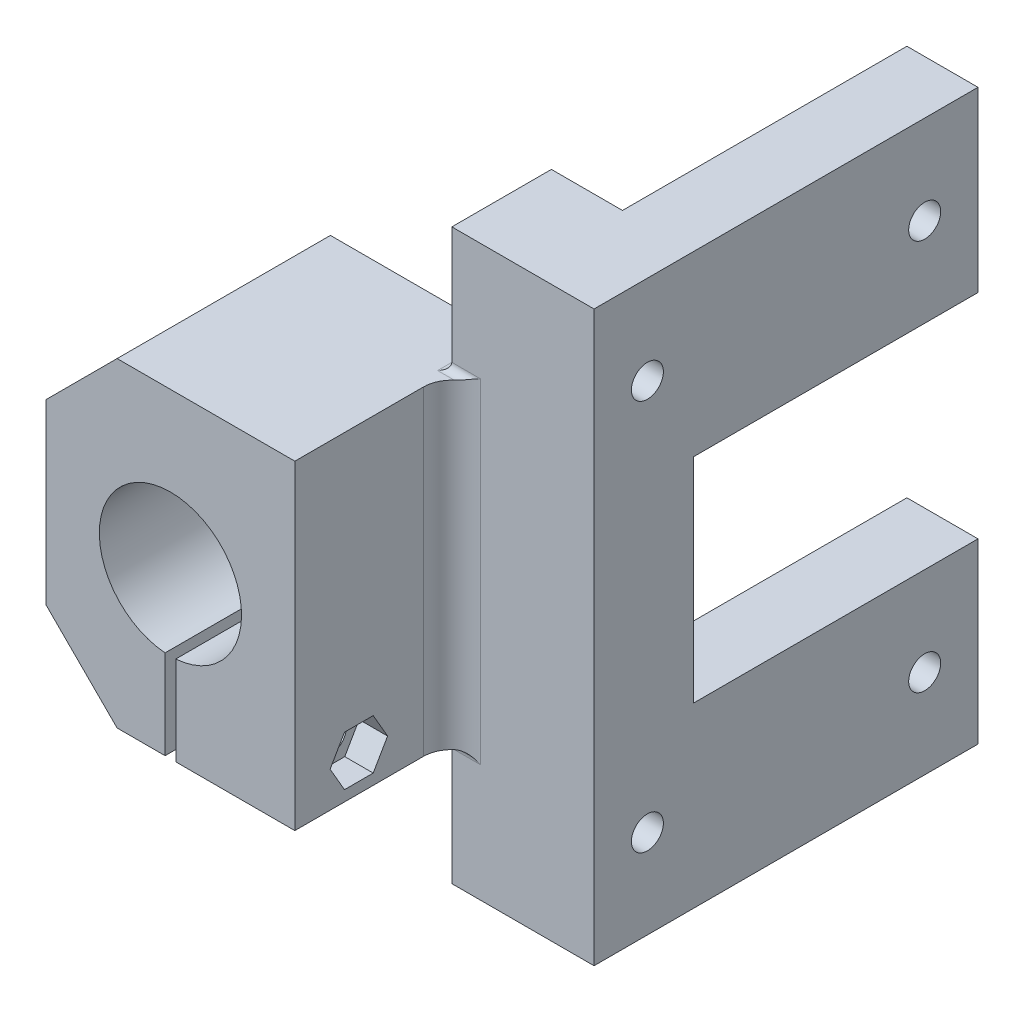
SolidWorks part; units mm, degrees
ref_plane "Plan de face" through (0, 0, 0) normal (0, 0, 1) x (1, 0, 0)
ref_plane "Plan de dessus" through (0, 0, 0) normal (0, 1, 0) x (1, 0, 0)
ref_plane "Plan de droite" through (0, 0, 0) normal (1, 0, 0) x (0, 0, -1)
sketch "Sketch1" plane through (0, 0, 0) normal (0, 0, 1) x (1, 0, 0)
  line L1 (17.5, -22.5) -> (-17.5, -22.5)
  line L2 (17.5, -22.5) -> (17.5, 22.5)
  line L3 (17.5, 22.5) -> (-17.5, 22.5)
  line L4 (-17.5, -22.5) -> (-17.5, 22.5)
  line L5 (17.5, -22.5) -> (-17.5, 22.5) construction
  line L6 (17.5, 22.5) -> (-17.5, -22.5) construction
  circle A0 centre (0, 0) radius 10
  dimension "D1" = 20
  dimension "D2" = 35
  dimension "D3" = 45
extrude "Boss-Extrude1" add sketch "Sketch1" along normal blind 30
sketch "Sketch2" plane through (17.5, 0, 0) normal (1, 0, 0) x (0, 0, -1)
  line L1 (-7.9199, -40) -> (46.0801, -40)
  line L2 (-7.9199, -40) -> (-7.9199, 40)
  line L3 (-7.9199, 40) -> (46.0801, 40)
  line L4 (46.0801, -40) -> (46.0801, 40)
  circle A0 centre (-0.4199, 27.5) radius 2.25
  circle A1 centre (38.5801, 27.5) radius 2.25
  circle A2 centre (38.5801, -27.5) radius 2.25
  circle A3 centre (-0.4199, -27.5) radius 2.25
extrude "Boss-Extrude2" add sketch "Sketch2" along normal blind 20
sketch "Sketch3" plane through (17.5, 0, 0) normal (-1, 0, 0) x (0, 0, 1)
  line L0 (7.9199, -40) -> (-46.0801, -40) construction
  line L1 (-46.0801, 40) -> (-6.0801, 40)
  line L2 (-46.0801, 40) -> (-46.0801, -40)
  line L3 (-46.0801, -40) -> (-6.0801, -40)
  line L4 (-6.0801, 40) -> (-6.0801, -40)
  dimension "D1" = 40
extrude "Cut-Extrude1" cut sketch "Sketch3" against normal blind 10
sketch "Sketch5" plane through (37.5, 0, 0) normal (1, 0, 0) x (0, 0, -1)
  line L0 (46.0801, -40) -> (46.0801, 40) construction
  line L1 (46.0801, -15) -> (6.0801, -15)
  line L2 (46.0801, -15) -> (46.0801, 15)
  line L3 (46.0801, 15) -> (6.0801, 15)
  line L4 (6.0801, -15) -> (6.0801, 15)
  line L5 (46.0801, 40) -> (-7.9199, 40) construction
  line L6 (-7.9199, -40) -> (46.0801, -40) construction
  point P6 (0, 0)
  point P7 (46.08, -14.2432)
  point P8 (46.08, -14.987)
  point P9 (46.08, -14.4378)
  dimension "D1" = 40
  dimension "D2" = 25
  dimension "D3" = 25
extrude "Cut-Extrude2" cut sketch "Sketch5" against normal blind 10
fillet "Fillet1" radius 4 2 edges at (17.5, 0, 7.9199) (17.5, 0, 0)
fillet "Fillet2" radius 1 4 edges at (17.5, -22.5, 1.96) (19.5, -22.5, 7.9199) (17.5, 22.5, 1.96) (19.5, 22.5, 7.9199)
chamfer "Chamfer1" distance 10 angle 45 2 edges at (-17.5, 22.5, 15) (-17.5, -22.5, 15)
sketch "Sketch6" plane through (17.5, 0, 0) normal (1, 0, 0) x (0, 0, -1)
  line L0 (-30, -22.5) -> (-11.9199, -22.5) construction
  line L1 (-18.9793, -21) -> (-16.9585, -17.5)
  line L2 (-16.9585, -17.5) -> (-18.9793, -14)
  line L3 (-18.9793, -14) -> (-23.0207, -14)
  line L4 (-23.0207, -14) -> (-25.0415, -17.5)
  line L5 (-25.0415, -17.5) -> (-23.0207, -21)
  line L6 (-23.0207, -21) -> (-18.9793, -21)
  line L7 (-30, -22.5) -> (-30, 22.5) construction
  circle A0 centre (-21, -17.5) radius 3.5 construction
  dimension "D1" = 7
  dimension "D2" = 5
  dimension "D3" = 9
extrude "Cut-Extrude3" cut sketch "Sketch6" against normal blind 4
ref_plane "Plane1" through (-7.5, 0, 0) normal (1, 0, 0) x (0, 0, -1)
hole_wizard "Chambrage pour vis à six pans creux M41" positions "Sketch9" profile "Sketch10" counterbore size "M4" standard "ISO"
sketch "Sketch9" plane through (-7.5, 0, 0) normal (1, 0, 0) x (0, 0, -1)
  line L0 (-30, -22.5) -> (-11.9199, -22.5) construction
  line L1 (-30, -22.5) -> (-30, 22.5) construction
  point P0 (-21, -17.5)
  point P10 (-22.1263, -17.9319)
  dimension "D1" = 5
  dimension "D2" = 9
sketch "Sketch10" plane through (-7.5, -17.5, 21) normal (0, 1, 0) x (0, 0, 1)
  line L0 (0, 0) -> (0, 45)
  line L1 (0, 45) -> (2.25, 45)
  line L3 (2.25, 45) -> (2.25, 4.4)
  line L4 (2.25, 4.4) -> (4, 4.4)
  line L5 (4, 4.4) -> (4, 0)
  line L7 (4, 0) -> (0, 0)
  line L11 (0, -6.35) -> (0, 107.95) construction
  dimension "Diamètre du perçage jusqu'au prochain" = 4.5
  dimension "Profondeur du perçage jusqu'au prochain" = 45
  dimension "Diamètre du chambrage" = 8
  dimension "Profondeur du chambrage" = 4.4
sketch "Sketch11" plane through (-7.5, 0, 0) normal (1, 0, 0) x (0, 0, -1)
  circle A0 centre (-21, -17.5) radius 4
  dimension "D1" = 8
extrude "Cut-Extrude4" cut sketch "Sketch11" against normal through all
sketch "Sketch12" plane through (0, 0, 30) normal (0, 0, 1) x (1, 0, 0)
  line L0 (0.75, -9.9718) -> (0.75, -31.545)
  line L3 (-0.75, -31.545) -> (0.75, -31.545)
  line L6 (-0.75, -31.545) -> (0, 0) construction
  line L8 (0, 0) -> (0.75, -31.545) construction
  line L9 (-0.75, -9.9718) -> (-0.75, -31.545)
  arc A2 (-0.75, -9.9718) -> (0.75, -9.9718) centre (0, 0) ccw
  point P0 (0, 0)
  dimension "D1" = 1.5
extrude "Cut-Extrude5" cut sketch "Sketch12" against normal through all
hole_wizard "Chambrage pour vis à six pans creux M42" positions "Sketch13" profile "Sketch14" counterbore size "M4" standard "ISO" end condition through all
sketch "Sketch13" plane through (17.5, 0, 0) normal (-1, 0, 0) x (0, 0, 1)
  point P0 (0.4199, -27.5)
  point P3 (0.4199, 27.5)
sketch "Sketch14" plane through (17.5, -27.5, 0.4199) normal (0, 1, 0) x (0, 0, 1)
  line L0 (0, 0) -> (0, 20)
  line L1 (0, 20) -> (2.25, 20)
  line L3 (2.25, 20) -> (2.25, 4.4)
  line L4 (2.25, 4.4) -> (4, 4.4)
  line L5 (4, 4.4) -> (4, 0)
  line L7 (4, 0) -> (0, 0)
  line L11 (0, -6.35) -> (0, 107.95) construction
  dimension "Diamètre du perçage jusqu'au prochain" = 4.5
  dimension "Profondeur du perçage jusqu'au prochain" = 20
  dimension "Diamètre du chambrage" = 8
  dimension "Profondeur du chambrage" = 4.4
hole_wizard "Chambrage pour vis à six pans creux M43" positions "Sketch15" profile "Sketch16" counterbore size "M4" standard "ISO" end condition through all
sketch "Sketch15" plane through (27.5, 0, 0) normal (-1, 0, 0) x (0, 0, 1)
  point P0 (-38.5801, 27.5)
  point P3 (-38.5801, -27.5)
sketch "Sketch16" plane through (27.5, 27.5, -38.5801) normal (0, 1, 0) x (0, 0, 1)
  line L0 (0, 0) -> (0, 10)
  line L1 (0, 10) -> (2.25, 10)
  line L3 (2.25, 10) -> (2.25, 4.4)
  line L4 (2.25, 4.4) -> (4, 4.4)
  line L5 (4, 4.4) -> (4, 0)
  line L7 (4, 0) -> (0, 0)
  line L11 (0, -6.35) -> (0, 107.95) construction
  dimension "Diamètre du perçage jusqu'au prochain" = 4.5
  dimension "Profondeur du perçage jusqu'au prochain" = 10
  dimension "Diamètre du chambrage" = 8
  dimension "Profondeur du chambrage" = 4.4
